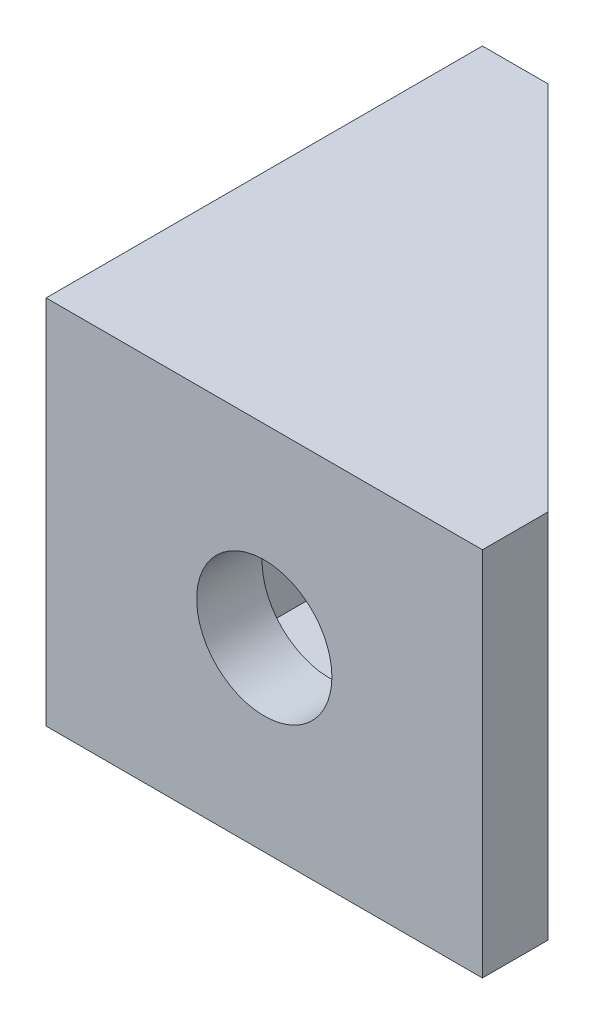
SolidWorks part; units mm, degrees
ref_plane "Front Plane" through (0, 0, 0) normal (0, 0, 1) x (1, 0, 0)
ref_plane "Top Plane" through (0, 0, 0) normal (0, 1, 0) x (1, 0, 0)
ref_plane "Right Plane" through (0, 0, 0) normal (1, 0, 0) x (0, 0, -1)
sketch "Sketch1" plane through (0, 0, 0) normal (0, 1, 0) x (1, 0, 0)
  line L1 (0, 0) -> (20, 0)
  line L2 (0, 0) -> (0, 20)
  line L3 (0, 20) -> (20, 20)
  line L4 (20, 0) -> (20, 20)
  dimension "D1" = 20
extrude "Boss-Extrude1" add sketch "Sketch1" along normal blind 17
sketch "Sketch2" plane through (0, 17, 0) normal (0, 1, 0) x (1, 0, 0)
  line L0 (3, 20) -> (20, 3)
  line L1 (20, 20) -> (0, 20) construction
  line L2 (20, 0) -> (20, 20) construction
  line L3 (3, 20) -> (0, 20) construction
  line L4 (3, 20) -> (20, 20)
  line L5 (20, 20) -> (20, 3)
  dimension "D1" = 45
  dimension "D2" = 3
extrude "Cut-Extrude1" cut sketch "Sketch2" against normal blind 17
sketch "Sketch3" plane through (0, 0, -20) normal (0, 0, -1) x (-1, 0, 0)
  line L0 (-3, 17) -> (-3, 15) construction
  line L1 (-3, 0) -> (-3, 17) construction
  line L2 (-20, 0) -> (-20, 17) construction
  line L3 (-3, 15) -> (-20, 15)
  line L4 (-3, 15) -> (-3, 2)
  line L5 (-3, 2) -> (-20, 2)
  line L6 (-20, 15) -> (-20, 2)
  dimension "D1" = 2
extrude "Cut-Extrude2" cut sketch "Sketch3" against normal blind 17
sketch "Sketch4" plane through (0, 0, 0) normal (-1, 0, 0) x (0, 0, 1)
  line L0 (-20, 17) -> (0, 0) construction
  line L1 (0, 17) -> (-20, 0) construction
  circle A0 centre (-10, 8.5) radius 3.1
extrude "Cut-Extrude3" cut sketch "Sketch4" against normal up to next
sketch "Sketch5" plane through (0, 0, 0) normal (0, 0, 1) x (1, 0, 0)
  line L0 (0, 17) -> (20, 0) construction
  line L1 (0, 0) -> (20, 17) construction
  circle A0 centre (10, 8.5) radius 3.1
  dimension "D1" = 6.2
extrude "Cut-Extrude4" cut sketch "Sketch5" against normal up to next
